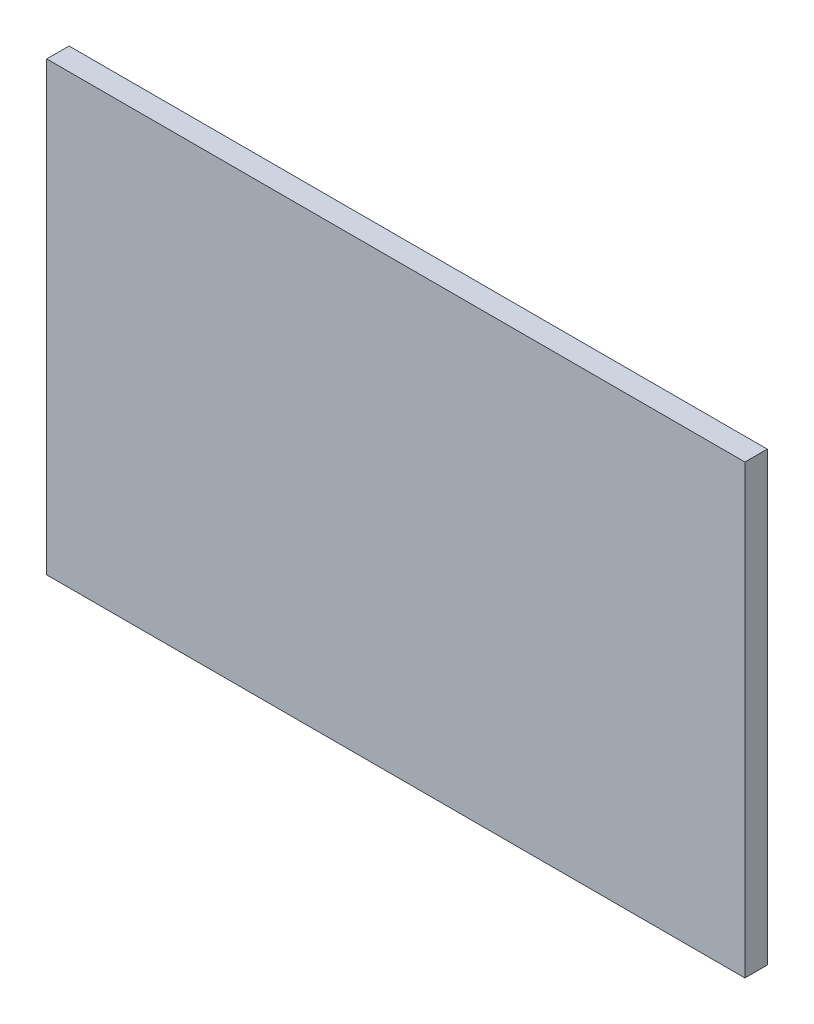
SolidWorks part; units mm, degrees
ref_plane "Plan de face" through (0, 0, 0) normal (0, 0, 1) x (1, 0, 0)
ref_plane "Plan de dessus" through (0, 0, 0) normal (0, 1, 0) x (1, 0, 0)
ref_plane "Plan de droite" through (0, 0, 0) normal (1, 0, 0) x (0, 0, -1)
sketch "Esquisse1" plane through (0, 0, 0) normal (0, 0, 1) x (1, 0, 0)
  line L1 (0, 0) -> (250, 0)
  line L2 (0, 0) -> (0, 160)
  line L3 (0, 160) -> (250, 160)
  line L4 (250, 0) -> (250, 160)
  dimension "D1" = 160
  dimension "D2" = 250
extrude "Boss.-Extru.1" add sketch "Esquisse1" along normal blind 8
